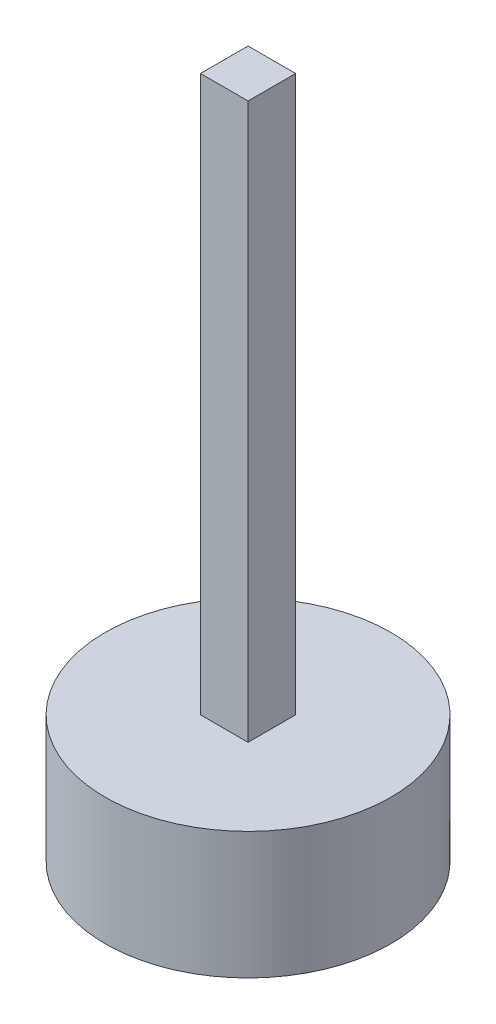
SolidWorks part; units mm, degrees
ref_plane "Front Plane" through (0, 0, 0) normal (0, 0, 1) x (1, 0, 0)
ref_plane "Top Plane" through (0, 0, 0) normal (0, 1, 0) x (1, 0, 0)
ref_plane "Right Plane" through (0, 0, 0) normal (1, 0, 0) x (0, 0, -1)
sketch "Sketch1" plane through (0, 0, 0) normal (0, 1, 0) x (1, 0, 0)
  line L1 (15, 0) -> (-15, 0)
  line L2 (15, 0) -> (15, 30)
  line L3 (15, 30) -> (-15, 30)
  line L4 (-15, 0) -> (-15, 30)
  dimension "D1" = 30
extrude "Boss-Extrude1" add sketch "Sketch1" against normal blind 350
sketch "Sketch2" plane through (0, -350, 0) normal (0, -1, 0) x (1, 0, 0)
  line L0 (0, 0) -> (0, -30)
  line L1 (-15, 0) -> (15, 0) construction
  line L2 (15, -30) -> (-15, -30) construction
  line L3 (-15, -15) -> (15, -15)
  line L4 (-15, -30) -> (-15, 0) construction
  line L5 (15, 0) -> (15, -30) construction
  circle A0 centre (0, -15) radius 90
  dimension "D1" = 180
extrude "Boss-Extrude2" add sketch "Sketch2" along normal blind 80 contours A0
sketch "Sketch3" plane through (0, -430, 0) normal (0, -1, 0) x (1, 0, 0)
  circle A0 centre (0, -15) radius 90 construction
  point P0 (0, -15)
